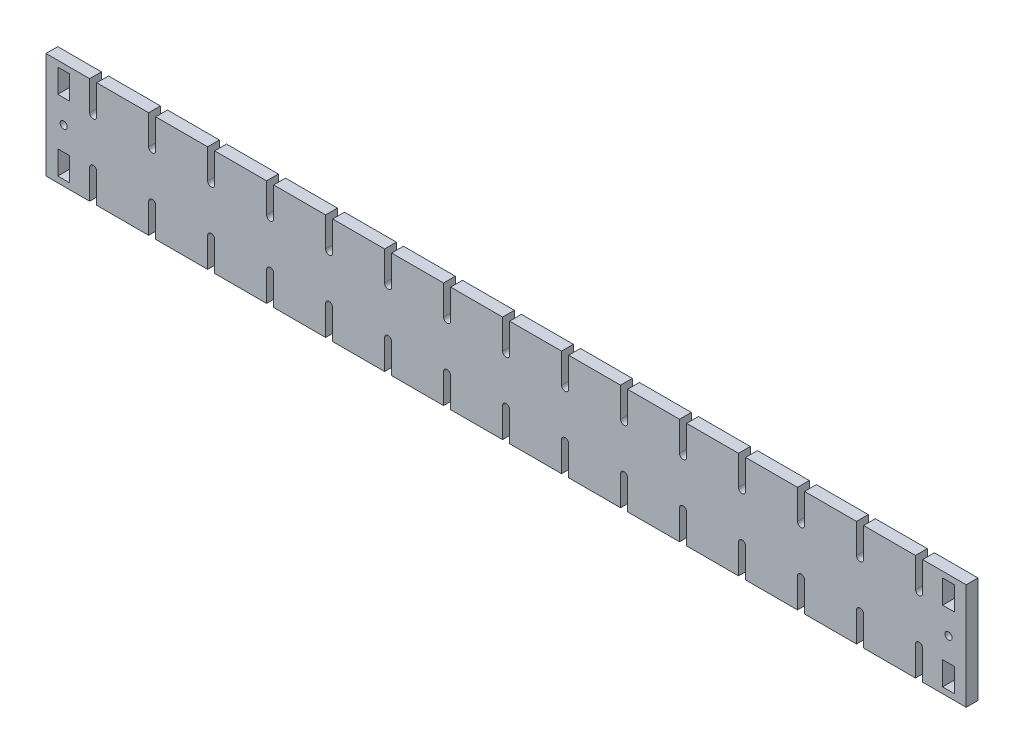
SolidWorks part; units mm, degrees
ref_plane "Front Plane" through (0, 0, 0) normal (0, 0, 1) x (1, 0, 0)
ref_plane "Top Plane" through (0, 0, 0) normal (0, 1, 0) x (1, 0, 0)
ref_plane "Right Plane" through (0, 0, 0) normal (1, 0, 0) x (0, 0, -1)
sketch "Sketch1" plane through (0, 0, 0) normal (0, 0, 1) x (1, 0, 0)
  line L0 (-90.218, 10) -> (299.3045, 10) construction
  line L1 (-85.8133, 22.5) -> (304.1867, 22.5)
  line L2 (-85.8133, 22.5) -> (-85.8133, -22.5)
  line L3 (-85.8133, -22.5) -> (304.1867, -22.5)
  line L4 (304.1867, 22.5) -> (304.1867, -22.5)
  line L5 (-80.8133, -10) -> (-75.8133, -10)
  line L6 (-91.3268, 0) -> (299.3045, 0) construction
  line L7 (-80.8133, 20) -> (-75.8133, 20)
  line L8 (-80.8133, 20) -> (-80.8133, 10)
  line L9 (-80.8133, 10) -> (-75.8133, 10)
  line L10 (-75.8133, 20) -> (-75.8133, 10)
  line L11 (-75.8133, -20) -> (-75.8133, -10)
  line L12 (-80.8133, -20) -> (-75.8133, -20)
  line L13 (-80.8133, -20) -> (-80.8133, -10)
  line L14 (109.1867, 30.0157) -> (109.1867, -45.8134) construction
  line L15 (-78.3133, 24.0051) -> (-78.3133, -32.23) construction
  line L16 (299.1867, -20) -> (299.1867, -10)
  line L17 (299.1867, -20) -> (294.1867, -20)
  line L18 (294.1867, -20) -> (294.1867, -10)
  line L19 (299.1867, -10) -> (294.1867, -10)
  line L20 (299.1867, 10) -> (294.1867, 10)
  line L21 (294.1867, 20) -> (294.1867, 10)
  line L22 (299.1867, 20) -> (294.1867, 20)
  line L23 (299.1867, 20) -> (299.1867, 10)
  circle A31 centre (-78.3133, 0) radius 1.5
  circle A32 centre (296.6867, 0) radius 1.5
  point P13 (-85.8133, 0)
  point P82 (-78.3133, 20)
  dimension "D1" = 45
  dimension "D2" = 390
  dimension "D3" = 12.5
  dimension "D4" = 10
  dimension "D7" = 5
  dimension "D8" = 5
extrude "Boss-Extrude1" add sketch "Sketch1" along normal blind 5
sketch "Sketch2" plane through (0, 0, 5) normal (0, 0, 1) x (1, 0, 0)
  line L0 (-65.8133, 26.1544) -> (-65.8133, -32.4929) construction
  line L1 (-85.8133, 22.5) -> (-85.8133, -22.5) construction
  line L2 (304.1867, 22.5) -> (-85.8133, 22.5) construction
  line L3 (-67.3133, 22.5) -> (-64.3133, 22.5)
  line L4 (-67.3133, 22.5) -> (-67.3133, 10)
  line L6 (-64.3133, 22.5) -> (-64.3133, 10)
  line L7 (-86.9763, 0) -> (351.4175, 0) construction
  line L8 (-42.3133, 22.5) -> (-39.3133, 22.5)
  line L9 (-42.3133, 22.5) -> (-42.3133, 10)
  line L10 (-39.3133, 22.5) -> (-39.3133, 10)
  line L11 (-17.3133, 22.5) -> (-14.3133, 22.5)
  line L12 (-17.3133, 22.5) -> (-17.3133, 10)
  line L13 (-14.3133, 22.5) -> (-14.3133, 10)
  line L14 (7.6867, 22.5) -> (10.6867, 22.5)
  line L15 (7.6867, 22.5) -> (7.6867, 10)
  line L16 (10.6867, 22.5) -> (10.6867, 10)
  line L17 (32.6867, 22.5) -> (35.6867, 22.5)
  line L18 (32.6867, 22.5) -> (32.6867, 10)
  line L19 (35.6867, 22.5) -> (35.6867, 10)
  line L20 (57.6867, 22.5) -> (60.6867, 22.5)
  line L21 (57.6867, 22.5) -> (57.6867, 10)
  line L22 (60.6867, 22.5) -> (60.6867, 10)
  line L23 (82.6867, 22.5) -> (85.6867, 22.5)
  line L24 (82.6867, 22.5) -> (82.6867, 10)
  line L25 (85.6867, 22.5) -> (85.6867, 10)
  line L26 (107.6867, 22.5) -> (110.6867, 22.5)
  line L27 (107.6867, 22.5) -> (107.6867, 10)
  line L28 (110.6867, 22.5) -> (110.6867, 10)
  line L29 (132.6867, 22.5) -> (135.6867, 22.5)
  line L30 (132.6867, 22.5) -> (132.6867, 10)
  line L31 (135.6867, 22.5) -> (135.6867, 10)
  line L32 (157.6867, 22.5) -> (160.6867, 22.5)
  line L33 (157.6867, 22.5) -> (157.6867, 10)
  line L34 (160.6867, 22.5) -> (160.6867, 10)
  line L35 (182.6867, 22.5) -> (185.6867, 22.5)
  line L36 (182.6867, 22.5) -> (182.6867, 10)
  line L37 (185.6867, 22.5) -> (185.6867, 10)
  line L38 (207.6867, 22.5) -> (210.6867, 22.5)
  line L39 (207.6867, 22.5) -> (207.6867, 10)
  line L40 (210.6867, 22.5) -> (210.6867, 10)
  line L41 (232.6867, 22.5) -> (235.6867, 22.5)
  line L42 (232.6867, 22.5) -> (232.6867, 10)
  line L43 (235.6867, 22.5) -> (235.6867, 10)
  line L44 (257.6867, 22.5) -> (260.6867, 22.5)
  line L45 (257.6867, 22.5) -> (257.6867, 10)
  line L46 (260.6867, 22.5) -> (260.6867, 10)
  line L47 (282.6867, 22.5) -> (285.6867, 22.5)
  line L48 (282.6867, 22.5) -> (282.6867, 10)
  line L49 (285.6867, 22.5) -> (285.6867, 10)
  line L50 (285.6867, -22.5) -> (285.6867, -10)
  line L51 (282.6867, -22.5) -> (282.6867, -10)
  line L52 (282.6867, -22.5) -> (285.6867, -22.5)
  line L53 (260.6867, -22.5) -> (260.6867, -10)
  line L54 (257.6867, -22.5) -> (257.6867, -10)
  line L55 (257.6867, -22.5) -> (260.6867, -22.5)
  line L56 (235.6867, -22.5) -> (235.6867, -10)
  line L57 (232.6867, -22.5) -> (232.6867, -10)
  line L58 (232.6867, -22.5) -> (235.6867, -22.5)
  line L59 (210.6867, -22.5) -> (210.6867, -10)
  line L60 (207.6867, -22.5) -> (207.6867, -10)
  line L61 (207.6867, -22.5) -> (210.6867, -22.5)
  line L62 (185.6867, -22.5) -> (185.6867, -10)
  line L63 (182.6867, -22.5) -> (182.6867, -10)
  line L64 (182.6867, -22.5) -> (185.6867, -22.5)
  line L65 (160.6867, -22.5) -> (160.6867, -10)
  line L66 (157.6867, -22.5) -> (157.6867, -10)
  line L67 (157.6867, -22.5) -> (160.6867, -22.5)
  line L68 (135.6867, -22.5) -> (135.6867, -10)
  line L69 (132.6867, -22.5) -> (132.6867, -10)
  line L70 (132.6867, -22.5) -> (135.6867, -22.5)
  line L71 (110.6867, -22.5) -> (110.6867, -10)
  line L72 (107.6867, -22.5) -> (107.6867, -10)
  line L73 (107.6867, -22.5) -> (110.6867, -22.5)
  line L74 (85.6867, -22.5) -> (85.6867, -10)
  line L75 (82.6867, -22.5) -> (82.6867, -10)
  line L76 (82.6867, -22.5) -> (85.6867, -22.5)
  line L77 (60.6867, -22.5) -> (60.6867, -10)
  line L78 (57.6867, -22.5) -> (57.6867, -10)
  line L79 (57.6867, -22.5) -> (60.6867, -22.5)
  line L80 (35.6867, -22.5) -> (35.6867, -10)
  line L81 (32.6867, -22.5) -> (32.6867, -10)
  line L82 (32.6867, -22.5) -> (35.6867, -22.5)
  line L83 (10.6867, -22.5) -> (10.6867, -10)
  line L84 (7.6867, -22.5) -> (7.6867, -10)
  line L85 (7.6867, -22.5) -> (10.6867, -22.5)
  line L86 (-14.3133, -22.5) -> (-14.3133, -10)
  line L87 (-17.3133, -22.5) -> (-17.3133, -10)
  line L88 (-17.3133, -22.5) -> (-14.3133, -22.5)
  line L89 (-39.3133, -22.5) -> (-39.3133, -10)
  line L90 (-42.3133, -22.5) -> (-42.3133, -10)
  line L91 (-42.3133, -22.5) -> (-39.3133, -22.5)
  line L92 (-64.3133, -22.5) -> (-64.3133, -10)
  line L93 (-67.3133, -22.5) -> (-67.3133, -10)
  line L94 (-67.3133, -22.5) -> (-64.3133, -22.5)
  arc A0 (-67.3133, 10) -> (-64.3133, 10) centre (-65.8133, 10) ccw
  arc A1 (-42.3133, 10) -> (-39.3133, 10) centre (-40.8133, 10) ccw
  arc A2 (-17.3133, 10) -> (-14.3133, 10) centre (-15.8133, 10) ccw
  arc A3 (7.6867, 10) -> (10.6867, 10) centre (9.1867, 10) ccw
  arc A4 (32.6867, 10) -> (35.6867, 10) centre (34.1867, 10) ccw
  arc A5 (57.6867, 10) -> (60.6867, 10) centre (59.1867, 10) ccw
  arc A6 (82.6867, 10) -> (85.6867, 10) centre (84.1867, 10) ccw
  arc A7 (107.6867, 10) -> (110.6867, 10) centre (109.1867, 10) ccw
  arc A8 (132.6867, 10) -> (135.6867, 10) centre (134.1867, 10) ccw
  arc A9 (157.6867, 10) -> (160.6867, 10) centre (159.1867, 10) ccw
  arc A10 (182.6867, 10) -> (185.6867, 10) centre (184.1867, 10) ccw
  arc A11 (207.6867, 10) -> (210.6867, 10) centre (209.1867, 10) ccw
  arc A12 (232.6867, 10) -> (235.6867, 10) centre (234.1867, 10) ccw
  arc A13 (257.6867, 10) -> (260.6867, 10) centre (259.1867, 10) ccw
  arc A14 (282.6867, 10) -> (285.6867, 10) centre (284.1867, 10) ccw
  arc A15 (282.6867, -10) -> (285.6867, -10) centre (284.1867, -10) cw
  arc A16 (257.6867, -10) -> (260.6867, -10) centre (259.1867, -10) cw
  arc A17 (232.6867, -10) -> (235.6867, -10) centre (234.1867, -10) cw
  arc A18 (207.6867, -10) -> (210.6867, -10) centre (209.1867, -10) cw
  arc A19 (182.6867, -10) -> (185.6867, -10) centre (184.1867, -10) cw
  arc A20 (157.6867, -10) -> (160.6867, -10) centre (159.1867, -10) cw
  arc A21 (132.6867, -10) -> (135.6867, -10) centre (134.1867, -10) cw
  arc A22 (107.6867, -10) -> (110.6867, -10) centre (109.1867, -10) cw
  arc A23 (82.6867, -10) -> (85.6867, -10) centre (84.1867, -10) cw
  arc A24 (57.6867, -10) -> (60.6867, -10) centre (59.1867, -10) cw
  arc A25 (32.6867, -10) -> (35.6867, -10) centre (34.1867, -10) cw
  arc A26 (7.6867, -10) -> (10.6867, -10) centre (9.1867, -10) cw
  arc A27 (-17.3133, -10) -> (-14.3133, -10) centre (-15.8133, -10) cw
  arc A28 (-42.3133, -10) -> (-39.3133, -10) centre (-40.8133, -10) cw
  arc A29 (-67.3133, -10) -> (-64.3133, -10) centre (-65.8133, -10) cw
  point P10 (-65.8133, 22.5)
  dimension "D1" = 20
  dimension "D2" = 3
  dimension "D3" = 15
extrude "Cut-Extrude1" cut sketch "Sketch2" against normal blind 5
